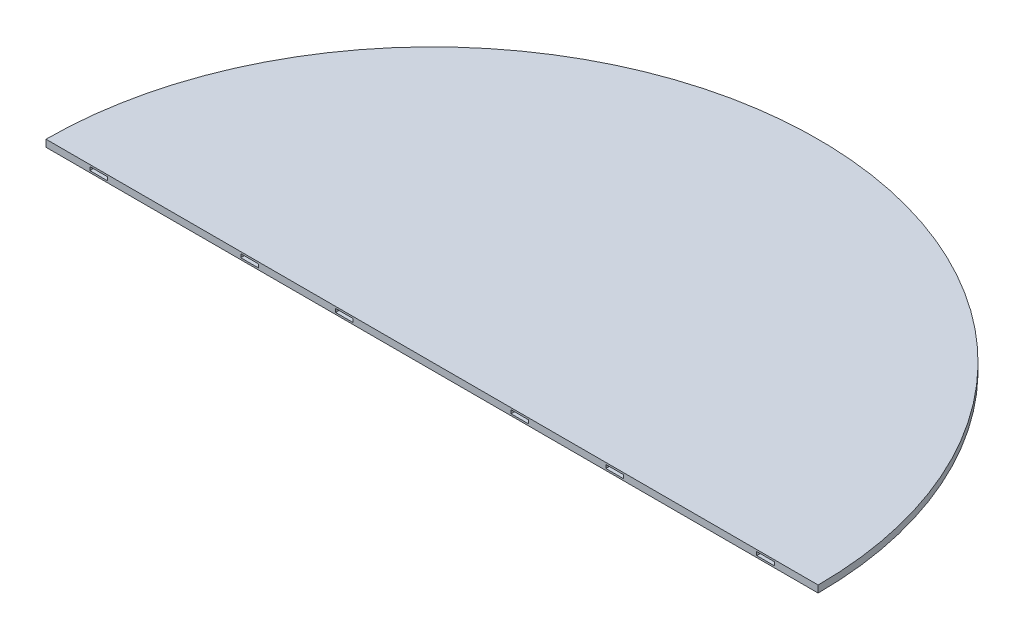
SolidWorks part; units mm, degrees
material "Pin"
material "AISI 1020 Acier laminé à froid"
material "AISI 1020 Acier laminé à froid"
ref_plane "Plan de face" through (0, 0, 0) normal (0, 0, 1) x (1, 0, 0)
ref_plane "Plan de dessus" through (0, 0, 0) normal (0, 1, 0) x (1, 0, 0)
ref_plane "Plan de droite" through (0, 0, 0) normal (1, 0, 0) x (0, 0, -1)
sketch "Esquisse1" plane through (0, 0, 0) normal (0, 1, 0) x (1, 0, 0)
  line L0 (-1100, 0) -> (1100, 0)
  arc A1 (1100, 0) -> (-1100, 0) centre (0, 0) ccw
  dimension "D1" = 1100
extrude "Boss.-Extru.1" add sketch "Esquisse1" along normal blind 20
ref_plane "Plan3" through (0, -17.5, 0) normal (0, -1, 0) x (-1, 0, 0)
sketch "Esquisse2" plane through (0, 0, 0) normal (0, -1, 0) x (1, 0, 0)
  circle A0 centre (0, 0) radius 5
sketch "Esquisse3" plane through (0, -17.5, 0) normal (0, -1, 0) x (1, 0, 0)
  line L0 (-601, -560.75) -> (-601, -260.25)
  line L1 (-601, -110) -> (-601, -410.5) construction
  line L2 (0, -560.75) -> (0, -260.25)
  line L3 (0, -800) -> (0, 400) construction
  line L4 (601, -560.75) -> (601, -260.25)
  line L5 (601, -110) -> (601, -410.5) construction
  point P6 (-601, -410.5)
  point P13 (0, -410.5)
  point P20 (601, -410.5)
other "Custom TUBE-CARRE-30-2(1)"
ref_plane "Plan1" through (-601, -17.5, -560.75) normal (0, 0, 1) x (-1, 0, 0)
sketch "Esquisse17" plane through (-601, -17.5, -560.75) normal (0, 0, 1) x (-1, 0, 0)
  line L1 (-11, -13) -> (11, -13)
  line L2 (-13, -11) -> (-13, 11)
  line L3 (-11, 13) -> (11, 13)
  line L4 (13, -11) -> (13, 11)
  line L5 (-13, -13) -> (13, 13) construction
  line L6 (-13, 13) -> (13, -13) construction
  line L7 (-13, -15) -> (13, -15)
  line L8 (-15, -13) -> (-15, 13)
  line L9 (-13, 15) -> (13, 15)
  line L10 (15, -13) -> (15, 13)
  line L11 (-15, -15) -> (15, 15) construction
  line L12 (-15, 15) -> (15, -15) construction
  arc A0 (13, -15) -> (15, -13) centre (13, -13) ccw
  arc A1 (11, -13) -> (13, -11) centre (11, -11) ccw
  arc A2 (-11, -13) -> (-13, -11) centre (-11, -11) cw
  arc A3 (-13, -15) -> (-15, -13) centre (-13, -13) cw
  arc A4 (13, 15) -> (15, 13) centre (13, 13) cw
  arc A5 (11, 13) -> (13, 11) centre (11, 11) cw
  arc A6 (-13, 11) -> (-11, 13) centre (-11, 11) cw
  arc A7 (-15, 13) -> (-13, 15) centre (-13, 13) cw
  point P0 (0, 0)
  point P6 (0, 0)
  point P35 (0, 15)
  point P36 (0, 13)
  point P37 (-13, 0)
  point P38 (-15, 0)
  point P39 (0, -15)
  point P40 (0, -13)
  point P41 (15, 0)
  point P42 (13, 0)
  point P43 (0, 0)
  point P44 (0, 0)
  dimension "D5" = 2
  dimension "D1" = 2
  dimension "D2" = 30
  dimension "D3" = 30
  dimension "D4" = 2
sketch "Esquisse12" plane through (0, -17.5, 0) normal (0, -1, 0) x (1, 0, 0)
  line L0 (-601, -415.5) -> (-601, -765.5)
  line L1 (-601, -560.75) -> (-601, -260.25) construction
  line L2 (0, -415.5) -> (0, -765.5)
  line L3 (0, -560.75) -> (0, -260.25) construction
  line L4 (0, -800) -> (0, 400) construction
  line L5 (601, -415.5) -> (601, -765.5)
  line L6 (601, -560.75) -> (601, -260.25) construction
  dimension "D1" = 350
  dimension "D2" = 5
other "Custom TUBE-CARRE-35-2.5(1)"
ref_plane "Plan2" through (-601, -17.5, -415.5) normal (0, 0, -1) x (1, 0, 0)
sketch "Esquisse111" plane through (-601, -17.5, -415.5) normal (0, 0, -1) x (1, 0, 0)
  line L1 (-13, -15) -> (13, -15)
  line L2 (-15, -13) -> (-15, 13)
  line L3 (-13, 15) -> (13, 15)
  line L4 (15, -13) -> (15, 13)
  line L5 (-15, -15) -> (15, 15) construction
  line L6 (-15, 15) -> (15, -15) construction
  line L7 (-15.5, -17.5) -> (15.5, -17.5)
  line L8 (-17.5, -15.5) -> (-17.5, 15.5)
  line L9 (-15.5, 17.5) -> (15.5, 17.5)
  line L10 (17.5, -15.5) -> (17.5, 15.5)
  line L11 (-17.5, -17.5) -> (17.5, 17.5) construction
  line L12 (-17.5, 17.5) -> (17.5, -17.5) construction
  arc A0 (15.5, -17.5) -> (17.5, -15.5) centre (15.5, -15.5) ccw
  arc A1 (13, -15) -> (15, -13) centre (13, -13) ccw
  arc A2 (-13, -15) -> (-15, -13) centre (-13, -13) cw
  arc A3 (-15.5, -17.5) -> (-17.5, -15.5) centre (-15.5, -15.5) cw
  arc A4 (15.5, 17.5) -> (17.5, 15.5) centre (15.5, 15.5) cw
  arc A5 (13, 15) -> (15, 13) centre (13, 13) cw
  arc A6 (-15, 13) -> (-13, 15) centre (-13, 13) cw
  arc A7 (-17.5, 15.5) -> (-15.5, 17.5) centre (-15.5, 15.5) cw
  point P0 (0, 0)
  point P6 (0, 0)
  point P35 (0, 17.5)
  point P36 (0, 15)
  point P37 (-15, 0)
  point P38 (-17.5, 0)
  point P39 (0, -15)
  point P40 (0, -17.5)
  point P41 (15, 0)
  point P42 (17.5, 0)
  point P43 (0, 0)
  dimension "D5" = 2
  dimension "D1" = 2.5
  dimension "D2" = 35
  dimension "D3" = 35
  dimension "D4" = 2.5
sketch "Esquisse113" plane through (0, 0, 0) normal (0, 0, 1) x (1, 0, 0)
  line L0 (-1100, 20) -> (-1100, 0) construction
  line L1 (-975, 5) -> (-925, 5)
  line L2 (-975, 5) -> (-975, 15)
  line L3 (-975, 15) -> (-925, 15)
  line L4 (-925, 5) -> (-925, 15)
  line L6 (-545, 15) -> (-495, 15)
  line L7 (-545, 15) -> (-545, 5)
  line L8 (-545, 5) -> (-495, 5)
  line L9 (-495, 15) -> (-495, 5)
  line L10 (-275, 15) -> (-225, 15)
  line L11 (-275, 15) -> (-275, 5)
  line L12 (-275, 5) -> (-225, 5)
  line L13 (-225, 15) -> (-225, 5)
  line L14 (225, 15) -> (275, 15)
  line L15 (225, 15) -> (225, 5)
  line L16 (225, 5) -> (275, 5)
  line L17 (275, 15) -> (275, 5)
  line L18 (495, 15) -> (545, 15)
  line L19 (495, 15) -> (495, 5)
  line L20 (495, 5) -> (545, 5)
  line L21 (545, 15) -> (545, 5)
  line L22 (925, 15) -> (975, 15)
  line L23 (925, 15) -> (925, 5)
  line L24 (925, 5) -> (975, 5)
  line L25 (975, 15) -> (975, 5)
  line L26 (1100, 20) -> (1100, 0) construction
  point P4 (-1100, 10)
  point P8 (-975, 10)
  point P28 (-950, 15)
  point P29 (950, 15)
  point P32 (520, 15)
  point P33 (250, 15)
  point P34 (-520, 15)
  point P35 (-250, 15)
  point P36 (0, 0)
  point P37 (0, 0)
  dimension "D1" = 50
  dimension "D2" = 10
  dimension "D3" = 150
  dimension "D4" = 50
  dimension "D5" = 50
  dimension "D6" = 50
  dimension "D7" = 50
  dimension "D8" = 50
  dimension "D9" = 150
  dimension "D10" = 430
  dimension "D11" = 270
  dimension "D12" = 430
  dimension "D13" = 270
extrude "Enlèv. mat.-Extru.1" cut sketch "Esquisse113" against normal blind 10
